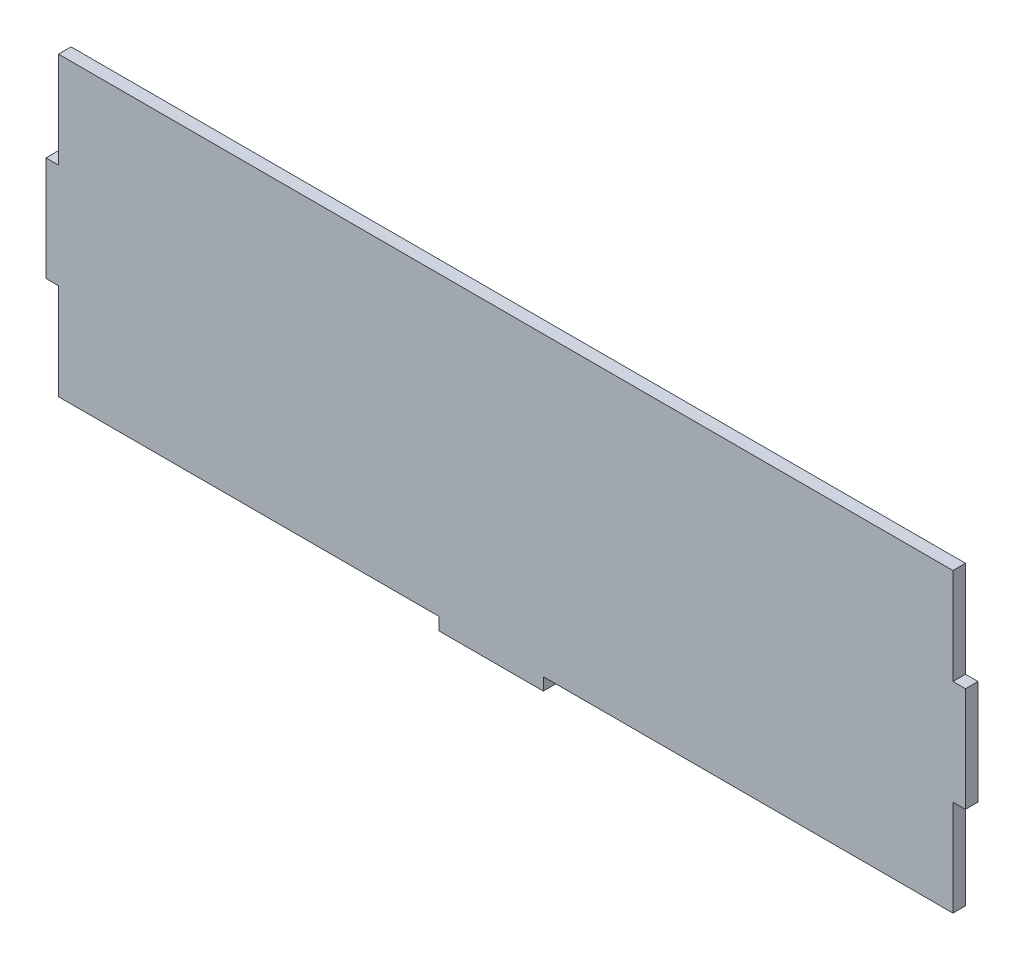
SolidWorks part; units mm, degrees
material "Maple"
ref_plane "Front Plane" through (0, 0, 0) normal (0, 0, 1) x (1, 0, 0)
ref_plane "Top Plane" through (0, 0, 0) normal (0, 1, 0) x (1, 0, 0)
ref_plane "Right Plane" through (0, 0, 0) normal (1, 0, 0) x (0, 0, -1)
sketch "Sketch1" plane through (0, 0, 0) normal (0, 0, 1) x (1, 0, 0)
  line L0 (214, 0) -> (214, -35) construction
  line L25 (0, 0) -> (428, 0)
  line L26 (0, 0) -> (0, -46)
  line L53 (0, -142) -> (182, -142)
  line L54 (428, 0) -> (428, -46)
  line L56 (182, -142) -> (182, -148)
  line L57 (182, -148) -> (232, -148)
  line L58 (232, -142) -> (232, -148)
  line L61 (428, -35) -> (214, -35) construction
  line L62 (0, -96) -> (0, -142)
  line L67 (434, -96) -> (428, -96)
  line L68 (434, -46) -> (434, -96)
  line L69 (-6, -46) -> (0, -46)
  line L70 (-6, -46) -> (-6, -96)
  line L71 (-6, -96) -> (0, -96)
  line L73 (-6, -46) -> (0, -35) construction
  line L74 (-6, -96) -> (0, -35) construction
  line L75 (434, -46) -> (428, -46)
  line L76 (428, -96) -> (428, -142)
  line L77 (232, -142) -> (428, -142)
  line L78 (214, -53) -> (214, -70) construction
  point P5 (214, -70)
  point P14 (27, -35)
  dimension "D1" = 428
  dimension "D2" = 142
  dimension "D3" = 50
  dimension "D4" = 46
  dimension "D5" = 46
  dimension "D6" = 182
  dimension "D7" = 50
  dimension "D8" = 50
  dimension "D9" = 6
  dimension "D10" = 6
  dimension "D11" = 6
extrude "Boss-Extrude1" add sketch "Sketch1" along normal blind 6
